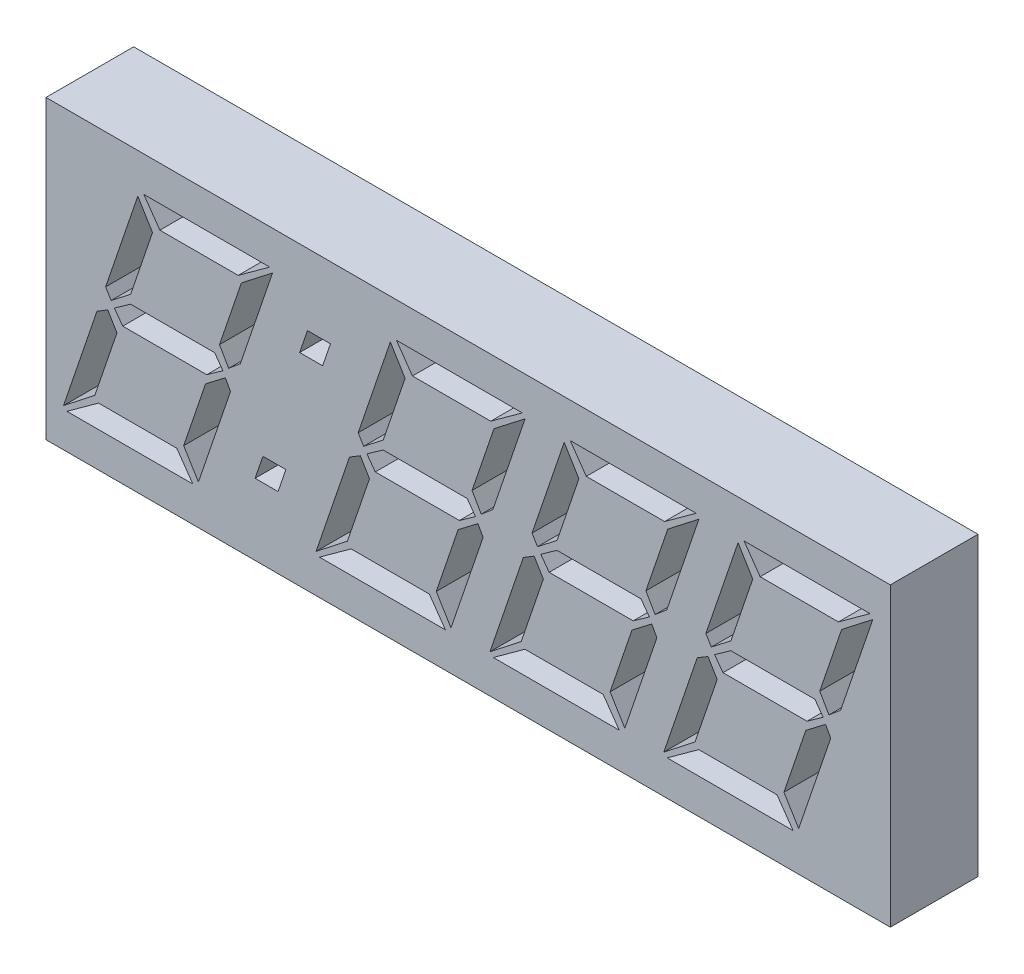
SolidWorks part; units mm, degrees
ref_plane "Спереди" through (0, 0, 0) normal (0, 0, 1) x (1, 0, 0)
ref_plane "Сверху" through (0, 0, 0) normal (0, 1, 0) x (1, 0, 0)
ref_plane "Справа" through (0, 0, 0) normal (1, 0, 0) x (0, 0, -1)
sketch "Эскиз1" plane through (0, 0, 0) normal (0, 0, 1) x (1, 0, 0)
  line L9 (65.1785, -93.2379) -> (565.1785, -93.2379)
  line L10 (65.1785, -93.2379) -> (65.1785, -313.2379)
  line L11 (65.1785, -313.2379) -> (565.1785, -313.2379)
  line L12 (565.1785, -93.2379) -> (565.1785, -313.2379)
  text T0 "<i>8:888</i>" font "DS-Digital" height 130
  dimension "D1" = 500
  dimension "D2" = 220
extrude "Бобышка-Вытянуть1" add sketch "Эскиз1" along normal blind 50
sketch "Эскиз2" plane through (0, 0, 50) normal (0, 0, 1) x (1, 0, 0)
  line L0 (225.057, -151.9154) -> (238.1505, -151.9154)
  line L1 (238.1505, -151.9154) -> (233.6789, -165.009)
  line L2 (233.6789, -165.009) -> (220.5853, -165.009)
  line L3 (220.5853, -165.009) -> (225.057, -151.9154)
  line L4 (199.6439, -226.7311) -> (212.7374, -226.7311)
  line L5 (212.7374, -226.7311) -> (208.2658, -239.8246)
  line L6 (208.2658, -239.8246) -> (195.1722, -239.8246)
  line L7 (195.1722, -239.8246) -> (199.6439, -226.7311)
  line L8 (303.7058, -260.4046) -> (231.896, -260.4046) construction
  dimension "D1" = 20.58
  dimension "D2" = 13.0935
  dimension "D3" = 13.836
  dimension "D4" = 0
extrude "Вырез-Вытянуть1" cut sketch "Эскиз2" against normal blind 65
sketch "Эскиз3" plane through (0, 0, 50) normal (0, 0, 1) x (1, 0, 0)
  line L1 (183.9606, -243.9126) -> (208.9541, -243.9126)
  line L2 (183.9606, -243.9126) -> (183.9606, -268.6669)
  line L3 (183.9606, -268.6669) -> (208.9541, -268.6669)
  line L4 (208.9541, -243.9126) -> (208.9541, -268.6669)
extrude "Бобышка-Вытянуть2" add sketch "Эскиз3" against normal blind 50
sketch "Эскиз4" plane through (0, 0, 50) normal (0, 0, 1) x (1, 0, 0)
  line L0 (131.7364, -131.3399) -> (203.5462, -131.3399) construction
  line L1 (67.9383, -94.3399) -> (565.4266, -94.3399)
  line L2 (67.9383, -94.3399) -> (67.9383, -297.4046)
  line L3 (67.9383, -297.4046) -> (565.4266, -297.4046)
  line L4 (565.4266, -94.3399) -> (565.4266, -297.4046)
  line L5 (159.6771, -260.4046) -> (87.8673, -260.4046) construction
  point P6 (0, 0)
  dimension "D1" = 37
  dimension "D2" = 37
  dimension "D3" = 18
  dimension "D4" = 18
extrude "Вырез-Вытянуть-Тонкостенный1" cut sketch "Эскиз4" against normal blind 84 thin thin type one direction wall 30
scale "Масштаб1" scale about centroid uniform scaling yes scale factor 1.5
sketch "Эскиз8" plane through (0, 0, 62.5) normal (0, 0, 1) x (1, 0, 0)
  line L0 (82.3709, -292.676) -> (-25.3438, -292.676) construction
  line L1 (-43.2372, -69.0789) -> (678.9952, -69.0789)
  line L2 (-43.2372, -69.0789) -> (-43.2372, -322.676)
  line L3 (-43.2372, -322.676) -> (678.9952, -322.676)
  line L4 (678.9952, -69.0789) -> (678.9952, -322.676)
  line L5 (40.46, -99.0789) -> (148.1747, -99.0789) construction
  dimension "D1" = 15
  dimension "D2" = 15
  dimension "D3" = 30
  dimension "D4" = 30
extrude "Вырез-Вытянуть-Тонкостенный2" cut sketch "Эскиз8" against normal blind 180 thin thin type one direction wall 50
